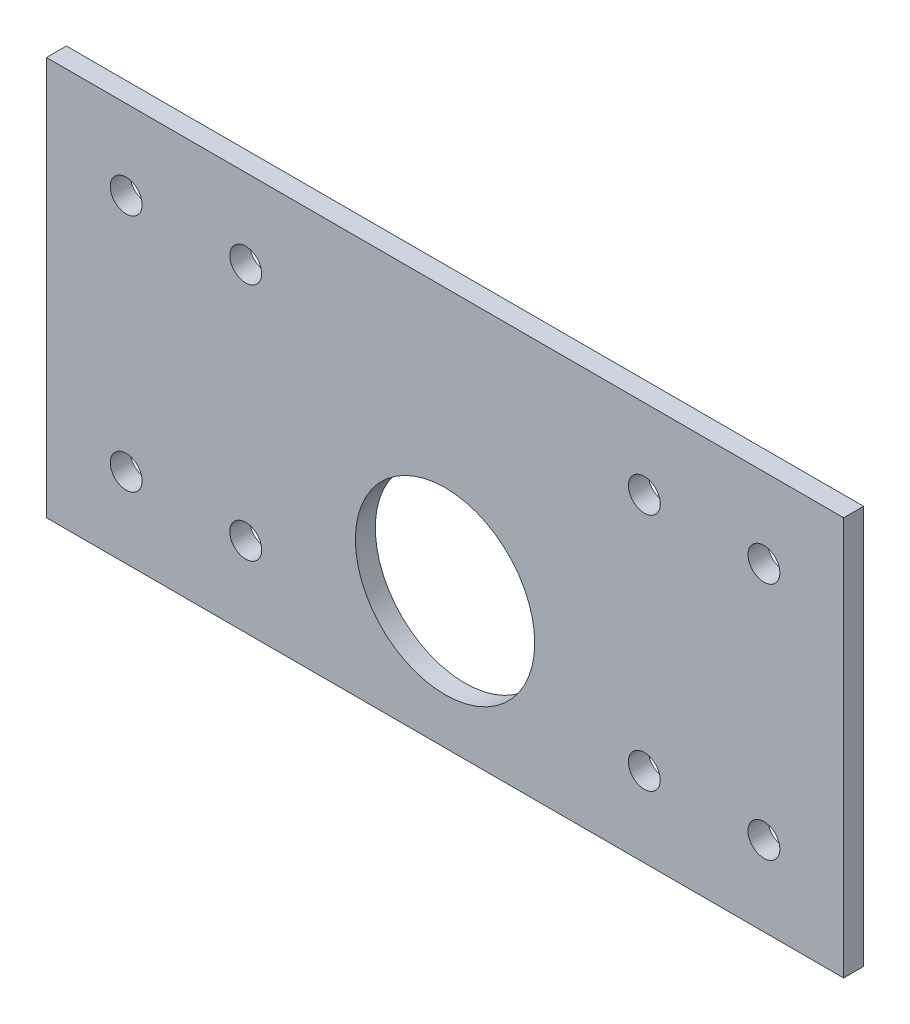
SolidWorks part; units mm, degrees
ref_plane "Front Plane" through (0, 0, 0) normal (0, 0, 1) x (1, 0, 0)
ref_plane "Top Plane" through (0, 0, 0) normal (0, 1, 0) x (1, 0, 0)
ref_plane "Right Plane" through (0, 0, 0) normal (1, 0, 0) x (0, 0, -1)
sketch "Sketch1" plane through (0, 0, 0) normal (0, 0, 1) x (1, 0, 0)
  line L0 (-63.5, 31.75) -> (63.5, -31.75) construction
  line L1 (-63.5, -31.75) -> (63.5, -31.75)
  line L2 (-63.5, -31.75) -> (-63.5, 31.75)
  line L3 (-63.5, 31.75) -> (63.5, 31.75)
  line L4 (63.5, -31.75) -> (63.5, 31.75)
  line L5 (-50.8, -19.05) -> (50.8, 19.05) construction
  line L6 (63.5, 31.75) -> (-63.5, -31.75) construction
  line L7 (50.8, -19.05) -> (-50.8, 19.05) construction
  line L8 (-50.8, -19.05) -> (-50.8, 19.05) construction
  line L9 (50.8, 19.05) -> (-50.8, 19.05) construction
  point P4 (-50.8, -11.9498)
  point P9 (0, 0)
  point P10 (-50.8, -19.05)
  dimension "D1" = 12.7
  dimension "D2" = 12.7
  dimension "D3" = 63.5
  dimension "D4" = 127
  dimension "D5" = 12.7
extrude "Boss-Extrude1" add sketch "Sketch1" along normal mid plane 3.175
sketch "Sketch3" plane through (0, 0, 1.5875) normal (0, 0, 1) x (1, 0, 0)
  circle A0 centre (0, -10.125) radius 14.2875
  dimension "D1" = 28.575
extrude "Cut-Extrude2" cut sketch "Sketch3" against normal through all both and the other way through all
sketch "Sketch4" plane through (0, 0, 0) normal (0, 0, 1) x (1, 0, 0)
  line L0 (63.5, 31.75) -> (-63.5, 31.75) construction
  line L1 (50.8, 19.05) -> (-50.8, 19.05) construction
  line L2 (50.8, 19.05) -> (50.8, -19.05) construction
  line L3 (50.8, -19.05) -> (-50.8, -19.05) construction
  line L4 (-50.8, 19.05) -> (-50.8, -19.05) construction
  line L5 (63.5, -31.75) -> (63.5, 31.75) construction
  line L6 (50.8, 19.05) -> (-50.8, -19.05) construction
  line L8 (50.8, -19.05) -> (-50.8, 19.05) construction
  circle A0 centre (-50.8, 19.05) radius 2.54
  circle A1 centre (-50.8, -19.05) radius 2.54
  circle A2 centre (50.8, -19.05) radius 2.54
  circle A3 centre (50.8, 19.05) radius 2.54
  point P0 (0, 0)
  point P6 (0, 0)
  point P15 (0, 0)
  point P18 (0, 0)
  point P19 (0, 0)
  point P20 (0, 0)
  dimension "D5" = 5.08
  dimension "D1" = 38.1
  dimension "D2" = 101.6
  dimension "D3" = 12.7
  dimension "D4" = 12.7
extrude "Cut-Extrude3" cut sketch "Sketch4" against normal through all both and the other way through all
sketch "Sketch5" plane through (0, 0, 0) normal (0, 0, 1) x (1, 0, 0)
  line L5 (-31.75, -19.05) -> (31.75, -19.05) construction
  line L6 (-31.75, -19.05) -> (-31.75, 19.05) construction
  line L7 (-31.75, 19.05) -> (31.75, 19.05) construction
  line L8 (31.75, -19.05) -> (31.75, 19.05) construction
  line L9 (-31.75, -19.05) -> (31.75, 19.05) construction
  line L10 (-31.75, 19.05) -> (31.75, -19.05) construction
  line L11 (-50.8, -19.05) -> (50.8, -19.05) construction
  line L12 (-50.8, -19.05) -> (-50.8, 19.05) construction
  line L13 (-50.8, 19.05) -> (50.8, 19.05) construction
  line L14 (50.8, -19.05) -> (50.8, 19.05) construction
  line L15 (-50.8, -19.05) -> (50.8, 19.05) construction
  line L16 (-50.8, 19.05) -> (50.8, -19.05) construction
  circle A0 centre (31.75, 19.05) radius 2.54
  circle A1 centre (-31.75, 19.05) radius 2.54
  circle A2 centre (-31.75, -19.05) radius 2.54
  circle A3 centre (31.75, -19.05) radius 2.54
  circle A4 centre (50.8, 19.05) radius 2.54 construction
  circle A5 centre (-50.8, -19.05) radius 2.54 construction
  circle A7 centre (-50.8, -19.05) radius 2.54 construction
  point P0 (0, 0)
  point P4 (0, 0)
  dimension "D1" = 19.05
extrude "Cut-Extrude4" cut sketch "Sketch5" against normal through all both and the other way through all
